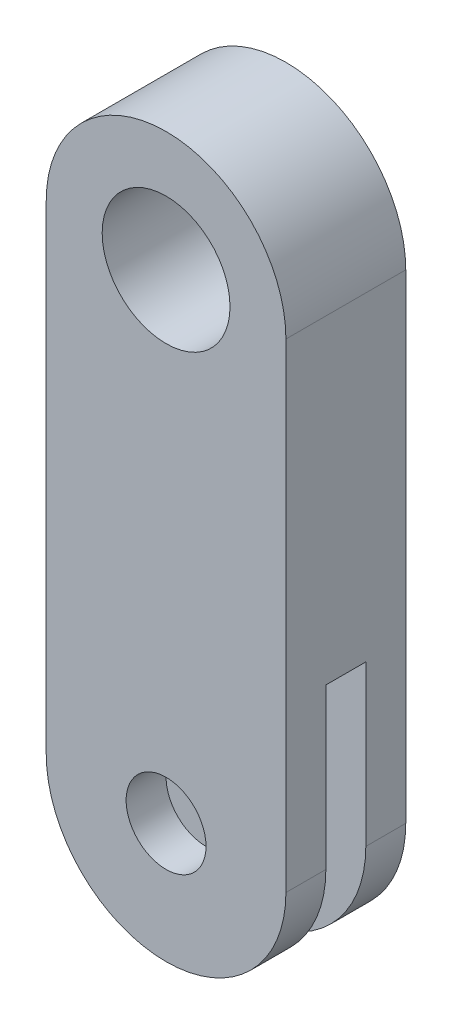
SolidWorks part; units mm, degrees
material "201 Annealed Stainless Steel (SS)"
ref_plane "Front Plane" through (0, 0, 0) normal (0, 0, 1) x (1, 0, 0)
ref_plane "Top Plane" through (0, 0, 0) normal (0, 1, 0) x (1, 0, 0)
ref_plane "Right Plane" through (0, 0, 0) normal (1, 0, 0) x (0, 0, -1)
sketch "Sketch3" plane through (0, 0, 0) normal (0, 0, 1) x (1, 0, 0)
  line L0 (-29.3341, 80.7958) -> (-29.3341, 20.7958)
  line L1 (0.6659, 20.7958) -> (0.6659, 80.7958)
  arc A0 (-29.3341, 20.7958) -> (0.6659, 20.7958) centre (-14.3341, 20.7958) ccw
  arc A1 (0.6659, 80.7958) -> (-29.3341, 80.7958) centre (-14.3341, 80.7958) ccw
  circle A3 centre (-14.3341, 20.7958) radius 5
  circle A5 centre (-14.3341, 80.7958) radius 8
  point P6 (0, 0)
extrude "Boss-Extrude1" add sketch "Sketch3" along normal blind 5
sketch "Sketch4" plane through (0, 0, 0) normal (0, 0, -1) x (-1, 0, 0)
  line L0 (29.3341, 80.7958) -> (29.3341, 40.7958)
  line L1 (-0.6659, 20.7958) -> (-0.6659, 80.7958) construction
  line L2 (29.3341, 80.7958) -> (29.3341, 20.7958) construction
  line L4 (29.3341, 40.7958) -> (-0.6659, 40.7958)
  line L5 (-0.6659, 40.7958) -> (-0.6659, 80.7958)
  circle A1 centre (14.3341, 80.7958) radius 8 construction
  circle A2 centre (14.3341, 20.7958) radius 5 construction
  circle A4 centre (14.3341, 80.7958) radius 8
  arc A5 (-0.6659, 80.7958) -> (29.3341, 80.7958) centre (14.3341, 80.7958) cw
  dimension "D2" = 20
extrude "Boss-Extrude4" add sketch "Sketch4" along normal blind 5
sketch "Sketch5" plane through (0, 0, -5) normal (0, 0, -1) x (-1, 0, 0)
  line L2 (29.3341, 20.7958) -> (29.3341, 80.7958)
  line L3 (-0.6659, 80.7958) -> (-0.6659, 20.7958)
  line L4 (29.3341, 20.7958) -> (29.3341, 80.7958)
  line L5 (-0.6659, 80.7958) -> (-0.6659, 20.7958)
  circle A1 centre (14.3341, 80.7958) radius 8
  circle A2 centre (14.3341, 80.7958) radius 8
  circle A3 centre (14.3341, 20.7958) radius 5
  circle A4 centre (14.3341, 20.7958) radius 5
  arc A6 (-0.6659, 20.7958) -> (29.3341, 20.7958) centre (14.3341, 20.7958) ccw
  arc A7 (29.3341, 80.7958) -> (-0.6659, 80.7958) centre (14.3341, 80.7958) ccw
  arc A8 (-0.6659, 20.7958) -> (29.3341, 20.7958) centre (14.3341, 20.7958) ccw
  arc A9 (29.3341, 80.7958) -> (-0.6659, 80.7958) centre (14.3341, 80.7958) ccw
  dimension "D1" = 0
  dimension "D2" = 0
  dimension "D3" = 0
extrude "Boss-Extrude5" add sketch "Sketch5" along normal blind 5
